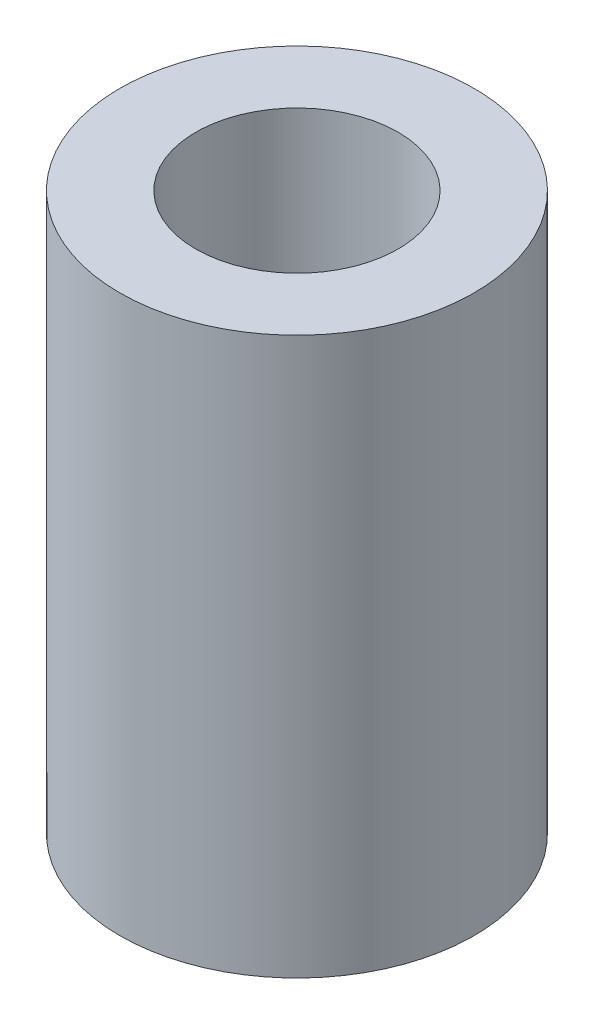
SolidWorks part; units mm, degrees
ref_plane "Front Plane" through (0, 0, 0) normal (0, 0, 1) x (1, 0, 0)
ref_plane "Top Plane" through (0, 0, 0) normal (0, 1, 0) x (1, 0, 0)
ref_plane "Right Plane" through (0, 0, 0) normal (1, 0, 0) x (0, 0, -1)
sketch "Sketch1" plane through (0, 0, 0) normal (0, 1, 0) x (1, 0, 0)
  circle A0 centre (0, 0) radius 2
  circle A1 centre (0, 0) radius 3.5
  dimension "D1" = 4
  dimension "D2" = 7
extrude "Boss-Extrude1" add sketch "Sketch1" along normal blind 11
